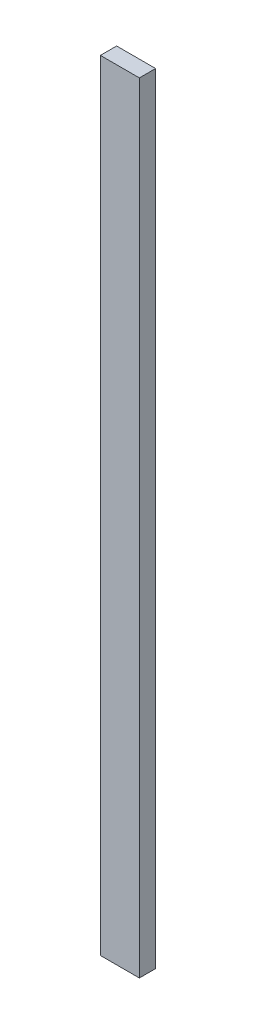
SolidWorks part; units mm, degrees
ref_plane "Plan de face" through (0, 0, 0) normal (0, 0, 1) x (1, 0, 0)
ref_plane "Plan de dessus" through (0, 0, 0) normal (0, 1, 0) x (1, 0, 0)
ref_plane "Plan de droite" through (0, 0, 0) normal (1, 0, 0) x (0, 0, -1)
sketch "Esquisse1" plane through (0, 0, 0) normal (0, 0, 1) x (1, 0, 0)
  line L1 (0, 0) -> (60, 0)
  line L2 (0, 0) -> (0, 1200)
  line L3 (0, 1200) -> (60, 1200)
  line L4 (60, 0) -> (60, 1200)
  dimension "D1" = 1200
  dimension "D2" = 60
extrude "Boss.-Extru.1" add sketch "Esquisse1" along normal blind 25
